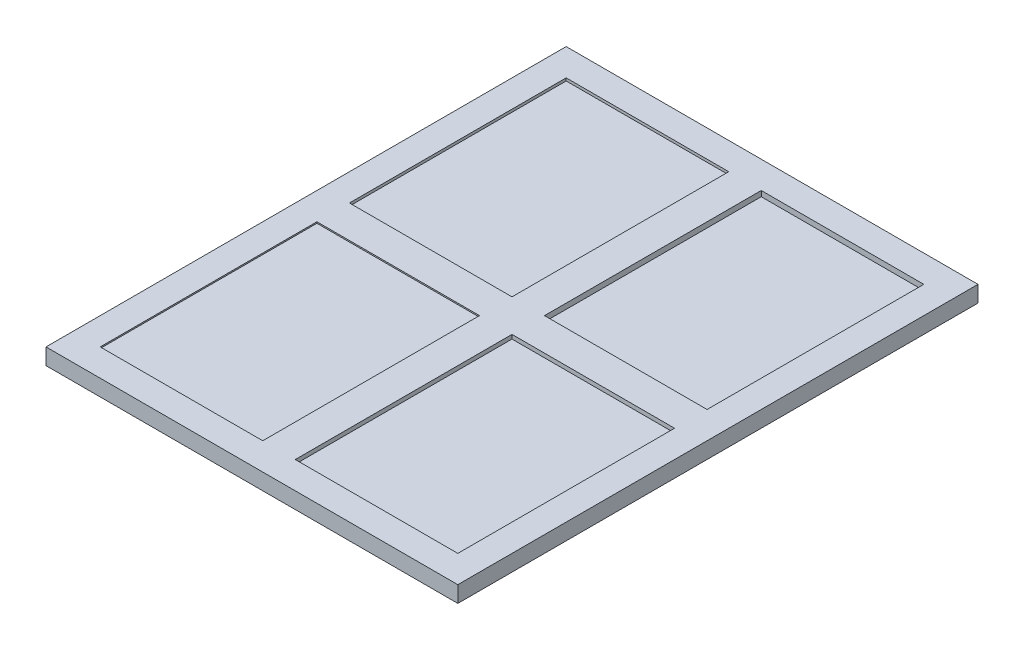
SolidWorks part; units mm, degrees
ref_plane "Front Plane" through (0, 0, 0) normal (0, 0, 1) x (1, 0, 0)
ref_plane "Top Plane" through (0, 0, 0) normal (0, 1, 0) x (1, 0, 0)
ref_plane "Right Plane" through (0, 0, 0) normal (1, 0, 0) x (0, 0, -1)
sketch "Sketch1" plane through (0, 0, 0) normal (0, 1, 0) x (1, 0, 0)
  line L0 (-38, 48) -> (38, 48)
  line L1 (-38, -48) -> (38, -48)
  line L5 (-33, 43) -> (-3, 43)
  line L6 (-33, 43) -> (-33, 3)
  line L7 (-33, 3) -> (-3, 3)
  line L8 (-3, 43) -> (-3, 3)
  line L9 (3, 43) -> (33, 43)
  line L10 (3, 43) -> (3, 3)
  line L11 (3, 3) -> (33, 3)
  line L12 (33, 43) -> (33, 3)
  line L13 (3, -3) -> (33, -3)
  line L14 (3, -3) -> (3, -43)
  line L15 (3, -43) -> (33, -43)
  line L16 (33, -3) -> (33, -43)
  line L17 (-33, -3) -> (-3, -3)
  line L18 (-33, -3) -> (-33, -43)
  line L19 (-33, -43) -> (-3, -43)
  line L20 (-3, -3) -> (-3, -43)
  line L22 (-38, 48) -> (-38, -48)
  line L23 (38, 48) -> (38, -48)
  dimension "D5" = 30
  dimension "D6" = 30
  dimension "D7" = 40
  dimension "D8" = 3
  dimension "D9" = 3
  dimension "D10" = 3
  dimension "D11" = 30
  dimension "D12" = 40
  dimension "D13" = 0
  dimension "D14" = 3
  dimension "D15" = 3
  dimension "D16" = 40
  dimension "D17" = 3
  dimension "D18" = 30
  dimension "D19" = 6
  dimension "D20" = 40
  dimension "D21" = 5
  dimension "D23" = 5
  dimension "D24" = 5
extrude "Boss-Extrude1" add sketch "Sketch1" along normal blind 0.25
sketch "Sketch2" plane through (0, 0, 0) normal (0, -1, 0) x (1, 0, 0)
  line L1 (38, -48) -> (-38, -48)
  line L2 (38, -48) -> (38, 48)
  line L3 (38, 48) -> (-38, 48)
  line L4 (-38, -48) -> (-38, 48)
extrude "Boss-Extrude2" add sketch "Sketch2" along normal blind 4
sketch "Sketch3" plane through (0, 0, 0) normal (0, 1, 0) x (1, 0, 0)
  line L0 (-33, 43) -> (-3, 43)
  line L1 (-3, 43) -> (-3, 3)
  line L2 (-3, 3) -> (-33, 3)
  line L3 (-33, 3) -> (-33, 43)
extrude "Cut-Extrude1" cut sketch "Sketch3" against normal blind 0.25
sketch "Sketch4" plane through (0, 0, 0) normal (0, 1, 0) x (1, 0, 0)
  line L1 (3, -3) -> (33, -3)
  line L2 (3, -3) -> (3, -43)
  line L3 (3, -43) -> (33, -43)
  line L4 (33, -3) -> (33, -43)
extrude "Cut-Extrude2" cut sketch "Sketch4" against normal blind 0.5
sketch "Sketch5" plane through (0, 0, 0) normal (0, 1, 0) x (1, 0, 0)
  line L1 (3, 43) -> (33, 43)
  line L2 (3, 43) -> (3, 3)
  line L3 (3, 3) -> (33, 3)
  line L4 (33, 43) -> (33, 3)
extrude "Cut-Extrude3" cut sketch "Sketch5" against normal blind 0.75
sketch "Sketch6" plane through (0, 0, 48) normal (0, 0, 1) x (1, 0, 0)
  line L1 (-41.8589, -2.75) -> (41.1474, -2.75)
  line L2 (-41.8589, -2.75) -> (-41.8589, -10.3392)
  line L3 (-41.8589, -10.3392) -> (41.1474, -10.3392)
  line L4 (41.1474, -2.75) -> (41.1474, -10.3392)
  line L5 (-38, 0.25) -> (38, 0.25) construction
  dimension "D1" = 3
extrude "Cut-Extrude4" cut sketch "Sketch6" against normal blind 107.75
